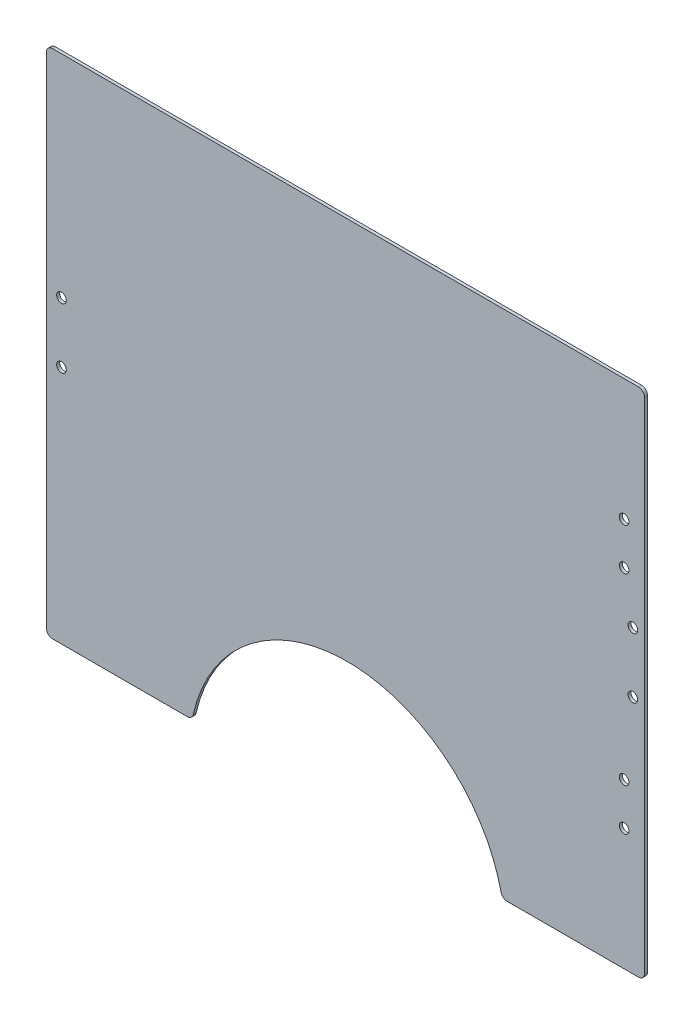
SolidWorks part; units mm, degrees
material "Thornel Mat VMA"
ref_plane "前视基准面" through (0, 0, 0) normal (0, 0, 1) x (1, 0, 0)
ref_plane "上视基准面" through (0, 0, 0) normal (0, 1, 0) x (1, 0, 0)
ref_plane "右视基准面" through (0, 0, 0) normal (1, 0, 0) x (0, 0, -1)
sketch "草图1" plane through (0, 0, 0) normal (0, 0, 1) x (1, 0, 0)
  line L1 (-100, -85) -> (100, -85)
  line L2 (-100, -85) -> (-100, 85)
  line L3 (-100, 85) -> (100, 85)
  line L4 (100, -85) -> (100, 85)
  line L5 (-100, -85) -> (100, 85) construction
  line L6 (-100, 85) -> (100, -85) construction
  point P0 (0, 0)
  dimension "D1" = 200
  dimension "D2" = 170
extrude "凸台-拉伸1" add sketch "草图1" along normal blind 1
sketch "草图2" plane through (0, 0, 0) normal (0, 0, -1) x (-1, 0, 0)
  circle A0 centre (0, -95) radius 52.5
  dimension "D2" = 105
  dimension "D1" = 95
extrude "切除-拉伸1" cut sketch "草图2" against normal blind 2
sketch "草图3" plane through (0, 0, 0) normal (0, 0, -1) x (-1, 0, 0)
  line L0 (0, 0) -> (95, 0) construction
  line L1 (95, 0) -> (95, -5.2775) construction
  line L2 (95, 0) -> (95, 14.7225) construction
  circle A2 centre (95, 14.7225) radius 1.6
  circle A3 centre (95, -5.2775) radius 1.6
  dimension "D4" = 3.2
  dimension "D1" = 95
  dimension "D2" = 14.7225
  dimension "D3" = 5.2775
extrude "切除-拉伸2" cut sketch "草图3" against normal blind 1
mirror "镜向1" about plane through (0, 0, 0) normal (1, 0, 0) of "切除-拉伸2"
sketch "草图4" plane through (0, 0, 0) normal (0, 0, -1) x (-1, 0, 0)
  line L0 (-100, -85) -> (-100, 85) construction
  line L1 (-100, -67) -> (-97.3, -67)
  line L2 (-100, -67) -> (-100, -40)
  line L3 (-100, -40) -> (-97.3, -40)
  line L4 (-97.3, -67) -> (-97.3, -40)
  line L5 (-100, 40) -> (-100, -40) construction
  line L6 (-100, 40) -> (-97.3, 40)
  line L7 (-100, 40) -> (-100, 67)
  line L8 (-100, 67) -> (-97.3, 67)
  line L9 (-97.3, 40) -> (-97.3, 67)
  point P10 (-100, 0)
  dimension "D1" = 2.7
  dimension "D2" = 27
  dimension "D3" = 80
extrude "切除-拉伸3" [suppressed] cut sketch "草图4" against normal blind 10
sketch "草图6" plane through (0, 0, 0) normal (0, 0, -1) x (-1, 0, 0)
  line L1 (-98.9, -85) -> (-100, -85)
  line L2 (-98.9, -85) -> (-98.9, 85)
  line L3 (-98.9, 85) -> (-100, 85)
  line L4 (-100, -85) -> (-100, 85)
  line L5 (-100, 85) -> (100, 85) construction
  line L6 (-100, -85) -> (-100, 85) construction
  line L7 (-51.5388, -85) -> (-100, -85) construction
  dimension "D1" = 1.1
extrude "切除-拉伸4" cut sketch "草图6" against normal blind 10
fillet "圆角1" radius 2 6 edges at (-100, -85, 0.5) (-100, 85, 0.5) (-51.5388, -85, 0.5) (51.5388, -85, 0.5) (98.9, 85, 0.5) (98.9, -85, 0.5)
sketch "草图8" plane through (0, 0, 0) normal (0, 0, -1) x (-1, 0, 0)
  circle A0 centre (-92.1, 44.5) radius 1.6
  circle A1 centre (-92.1, 30.5) radius 1.6
  circle A2 centre (-92.1, -30.5) radius 1.6
  circle A3 centre (-92.1, -44.5) radius 1.6
  dimension "D1" = 3.2
extrude "切除-拉伸5" cut sketch "草图8" against normal blind 10
